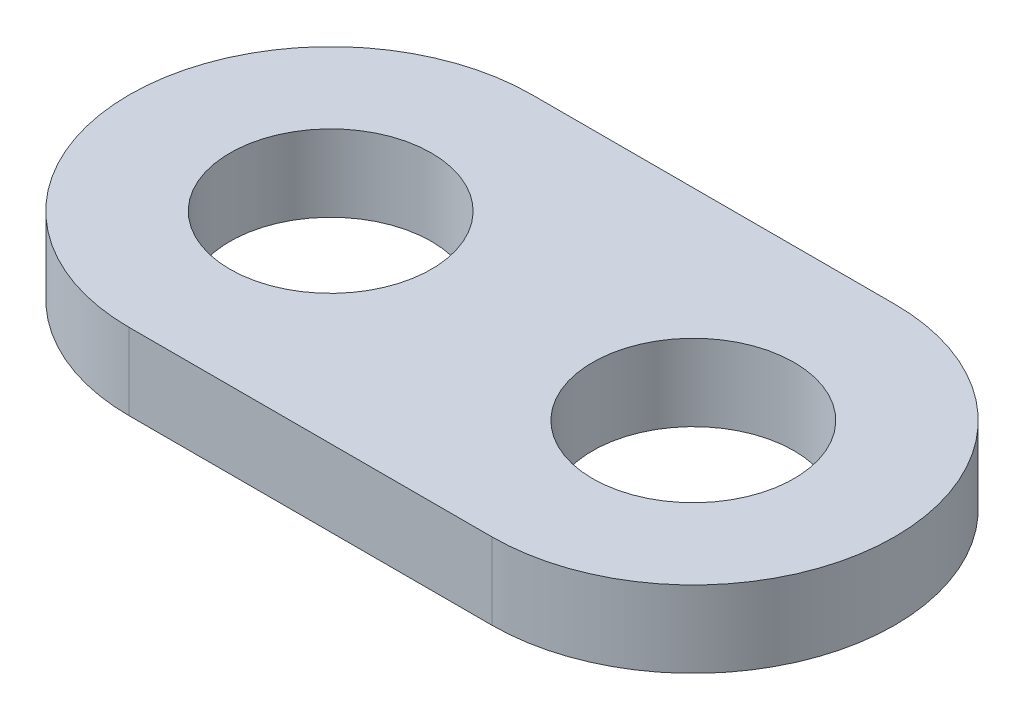
SolidWorks part; units mm, degrees
ref_plane "Front Plane" through (0, 0, 0) normal (0, 0, 1) x (1, 0, 0)
ref_plane "Top Plane" through (0, 0, 0) normal (0, 1, 0) x (1, 0, 0)
ref_plane "Right Plane" through (0, 0, 0) normal (1, 0, 0) x (0, 0, -1)
sketch "Sketch1" plane through (0, 0, 0) normal (0, 1, 0) x (1, 0, 0)
  line L0 (0, 0) -> (11.43, 0) construction
  line L1 (0, 6.35) -> (11.43, 6.35)
  line L2 (0, -6.35) -> (11.43, -6.35)
  arc A0 (0, 6.35) -> (0, -6.35) centre (0, 0) ccw
  arc A1 (11.43, -6.35) -> (11.43, 6.35) centre (11.43, 0) ccw
  circle A2 centre (0, 0) radius 3.175
  circle A3 centre (11.43, 0) radius 3.175
  point P3 (5.715, 0)
  dimension "D2" = 6.35
  dimension "D3" = 6.35
  dimension "D1" = 11.43
extrude "Boss-Extrude1" add sketch "Sketch1" along normal blind 2.413
